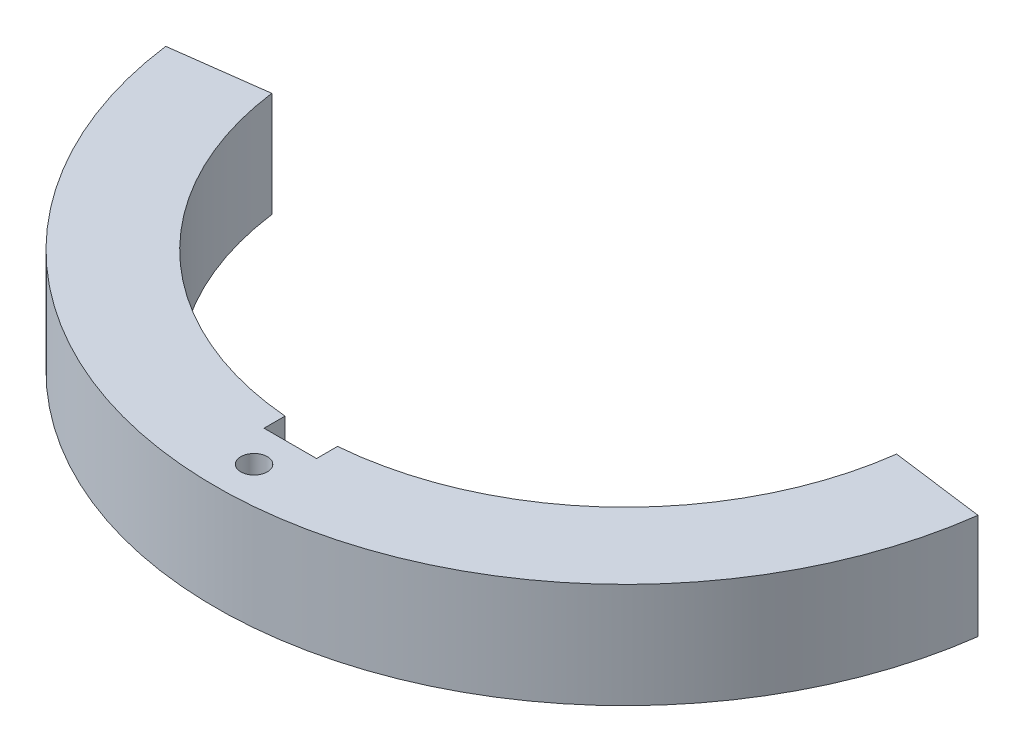
SolidWorks part; units mm, degrees
ref_plane "Front Plane" through (0, 0, 0) normal (0, 0, 1) x (1, 0, 0)
ref_plane "Top Plane" through (0, 0, 0) normal (0, 1, 0) x (1, 0, 0)
ref_plane "Right Plane" through (0, 0, 0) normal (1, 0, 0) x (0, 0, -1)
sketch "Sketch1" plane through (0, 0, 0) normal (0, 1, 0) x (1, 0, 0)
  line L0 (-3.175, -37.9675) -> (-3.175, 37.9675)
  line L3 (3.175, -37.9675) -> (3.175, 37.9675)
  line L4 (-3.164, -37.9684) -> (3.175, 38.1) construction
  line L5 (-3.164, 37.9684) -> (3.164, -37.9684) construction
  circle A0 centre (0, 0) radius 49.53
  circle A1 centre (0, 0) radius 38.1
  dimension "D1" = 99.06
  dimension "D2" = 76.2
  dimension "D3" = 6.35
extrude "Boss-Extrude1" add sketch "Sketch1" along normal blind 12.7 contours A0 A1 | L3 A1 L0
sketch "Sketch7" plane through (0, 0, 0) normal (0, -1, 0) x (1, 0, 0)
  line L0 (-37.774, -4.973) -> (-49.1063, -6.465)
  line L1 (54.483, 0) -> (-54.483, 0) construction
  line L2 (-37.774, 4.973) -> (-49.1063, 6.465)
  line L3 (0, -54.483) -> (0, 54.483) construction
  line L4 (37.774, 4.973) -> (49.1063, 6.465)
  line L5 (37.774, -4.973) -> (49.1063, -6.465)
  arc A0 (-49.1063, 6.465) -> (-49.1063, -6.465) centre (0, 0) ccw
  arc A2 (-37.774, 4.973) -> (-37.774, -4.973) centre (0, 0) ccw
  arc A4 (37.774, 4.973) -> (37.774, -4.973) centre (0, 0) cw
  arc A5 (49.1063, 6.465) -> (49.1063, -6.465) centre (0, 0) cw
extrude "Cut-Extrude1" cut sketch "Sketch7" against normal through all and the other way through all
sketch "Sketch8" plane through (0, 12.7, 0) normal (0, 1, 0) x (1, 0, 0)
  line L1 (3.175, 37.9675) -> (-3.175, 37.9675)
  line L2 (3.175, 37.9675) -> (3.175, -37.9675)
  line L3 (3.175, -37.9675) -> (-3.175, -37.9675)
  line L4 (-3.175, 37.9675) -> (-3.175, -37.9675)
extrude "Cut-Extrude3" cut sketch "Sketch8" against normal through all
sketch "Sketch9" plane through (0, 0, 37.9675) normal (0, 0, -1) x (-1, 0, 0)
  line L1 (-3.175, 0) -> (3.175, 0)
  line L2 (-3.175, 0) -> (-3.175, 12.7)
  line L3 (-3.175, 12.7) -> (3.175, 12.7)
  line L4 (3.175, 0) -> (3.175, 12.7)
extrude "Cut-Extrude4" cut sketch "Sketch9" against normal blind 2.54
sketch "Sketch10" plane through (0, 12.7, 0) normal (0, 1, 0) x (1, 0, 0)
  circle A0 centre (0, -44.885) radius 1.6
  dimension "D1" = 3.2
extrude "Cut-Extrude5" cut sketch "Sketch10" against normal blind 5.08
